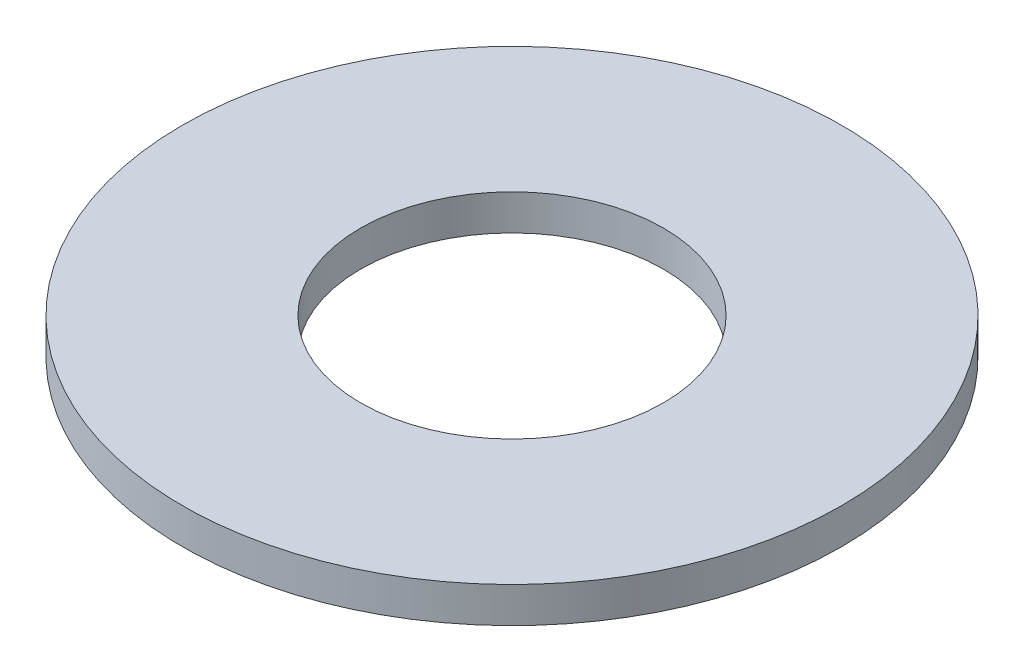
SolidWorks part; units mm, degrees
material "Plain Carbon Steel"
ref_plane "Front Plane" through (0, 0, 0) normal (0, 0, 1) x (1, 0, 0)
ref_plane "Top Plane" through (0, 0, 0) normal (0, 1, 0) x (1, 0, 0)
ref_plane "Right Plane" through (0, 0, 0) normal (1, 0, 0) x (0, 0, -1)
sketch "Sketch1" plane through (0, 0, 0) normal (0, 1, 0) x (1, 0, 0)
  circle A0 centre (0, 0) radius 4.25
  dimension "D1" = 8.5
extrude "Extrude-Thin1" add sketch "Sketch1" along normal blind 1 thin
